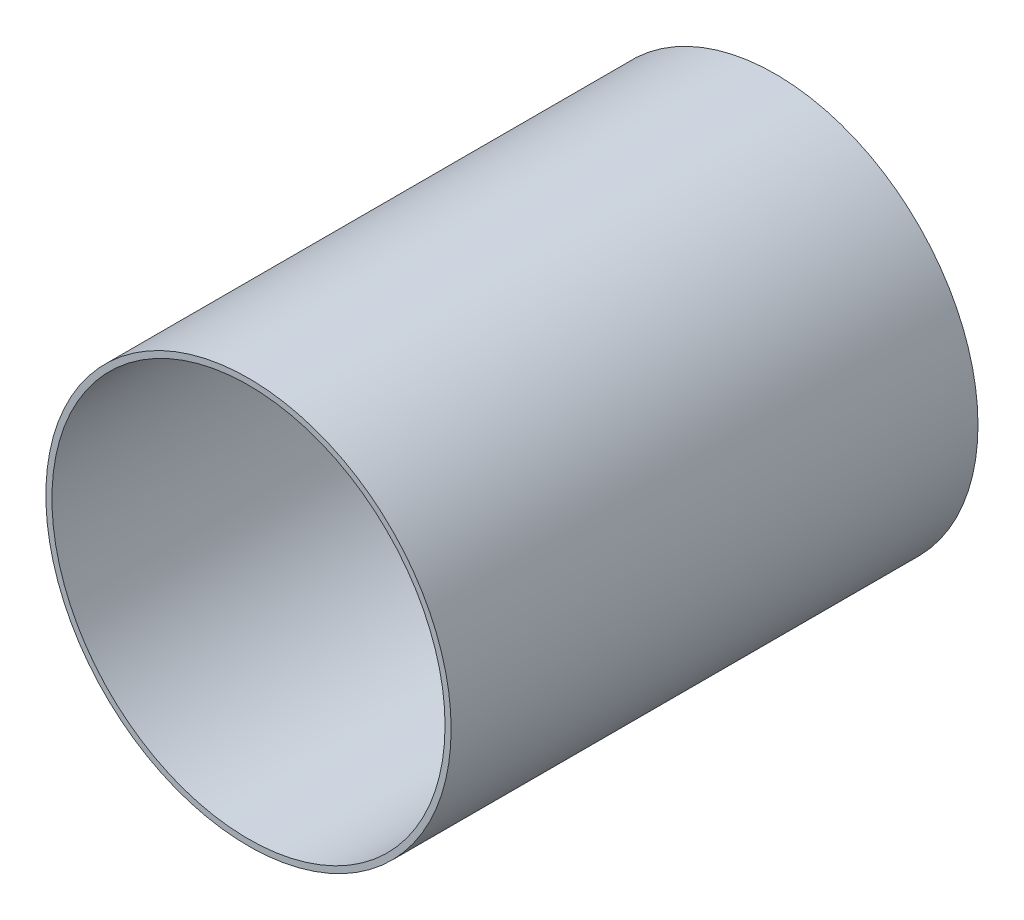
SolidWorks part; units mm, degrees
ref_plane "前视基准面" through (0, 0, 0) normal (0, 0, 1) x (1, 0, 0)
ref_plane "上视基准面" through (0, 0, 0) normal (0, 1, 0) x (1, 0, 0)
ref_plane "右视基准面" through (0, 0, 0) normal (1, 0, 0) x (0, 0, -1)
sketch "草图1" plane through (0, 0, 0) normal (0, 0, 1) x (1, 0, 0)
  circle A0 centre (0, 0) radius 50
  dimension "D1" = 100
extrude "凸台-拉伸1" add sketch "草图1" along normal blind 130
sketch "草图2" plane through (0, 0, 0) normal (0, 0, 1) x (1, 0, 0)
  circle A0 centre (0, 0) radius 48.5
  dimension "D1" = 97
extrude "切除-拉伸1" cut sketch "草图2" along normal blind 193
